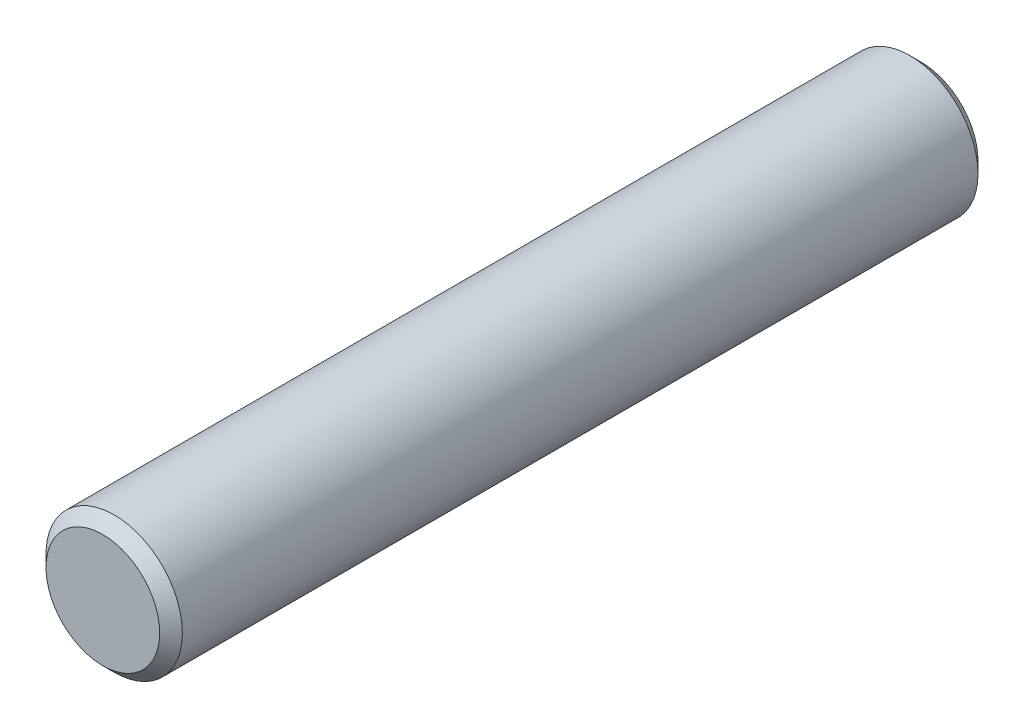
SolidWorks part; units mm, degrees
ref_plane "Front Plane" through (0, 0, 0) normal (0, 0, 1) x (1, 0, 0)
ref_plane "Top Plane" through (0, 0, 0) normal (0, 1, 0) x (1, 0, 0)
ref_plane "Right Plane" through (0, 0, 0) normal (1, 0, 0) x (0, 0, -1)
sketch "Sketch1" plane through (0, 0, 0) normal (0, 0, 1) x (1, 0, 0)
  circle A0 centre (0, 0) radius 3
  dimension "D1" = 6
extrude "Boss-Extrude1" add sketch "Sketch1" along normal blind 36
chamfer "Chamfer1" distance 0.5 angle 45 2 edges at (3, 0, 0) (3, 0, 36)
